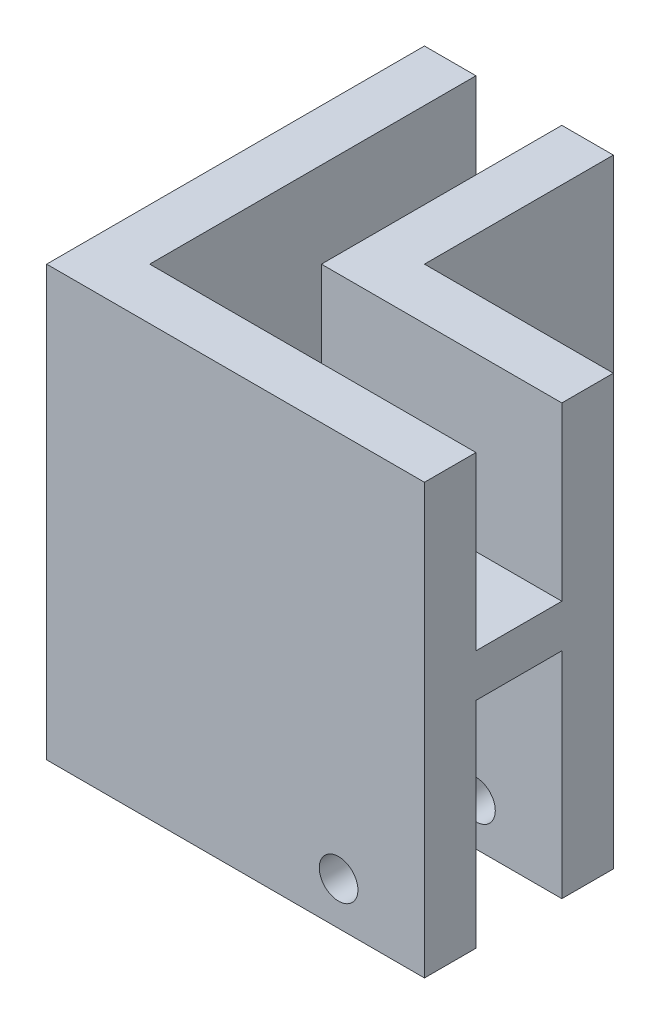
SolidWorks part; units mm, degrees
material "ABS"
ref_plane "Piano frontale" through (0, 0, 0) normal (0, 0, 1) x (1, 0, 0)
ref_plane "Piano superiore" through (0, 0, 0) normal (0, 1, 0) x (1, 0, 0)
ref_plane "Piano destro" through (0, 0, 0) normal (1, 0, 0) x (0, 0, -1)
sketch "Schizzo2" plane through (0, 0, 0) normal (0, 0, 1) x (1, 0, 0)
  line L0 (0, 0) -> (-10, 0)
  line L1 (-10, 0) -> (-10, -25)
  line L2 (-10, -25) -> (-16, -25)
  line L3 (-16, -25) -> (-16, 25)
  line L4 (-16, 25) -> (-10, 25)
  line L5 (-10, 25) -> (-10, 5)
  line L6 (-10, 5) -> (0, 5)
  line L7 (0, 5) -> (0, 25)
  line L8 (0, 25) -> (6, 25)
  line L9 (6, 25) -> (6, -25)
  line L10 (6, -25) -> (0, -25)
  line L11 (0, -25) -> (0, 0)
  dimension "D1" = 5
  dimension "D2" = 50
  dimension "D3" = 6
  dimension "D4" = 10
  dimension "D5" = 25
extrude "Estrusione-Estrusione1" add sketch "Schizzo2" along normal blind 28
sketch "Schizzo3" plane through (6, 0, 0) normal (1, 0, 0) x (0, 0, -1)
  line L3 (-28, 0) -> (-38, 0)
  line L4 (-38, 0) -> (-38, -25)
  line L5 (-38, -25) -> (-44, -25)
  line L6 (-44, -25) -> (-44, 25)
  line L7 (-44, 25) -> (-38, 25)
  line L8 (-38, 25) -> (-38, 5)
  line L9 (-38, 5) -> (-28, 5)
  line L12 (-28, -25) -> (-28, 25) construction
  line L13 (-38, 25) -> (-28, 25) construction
  line L14 (-28, 5) -> (-28, 0)
  dimension "D1" = 5
  dimension "D2" = 6
  dimension "D3" = 50
  dimension "D4" = 10
  dimension "D5" = 25
extrude "Estrusione-Estrusione2" add sketch "Schizzo3" against normal blind 16
sketch "Schizzo4" plane through (-10, 0, 0) normal (-1, 0, 0) x (0, 0, 1)
  line L0 (28, 25) -> (44, 25)
  line L1 (44, 25) -> (44, -25)
  line L2 (44, -25) -> (28, -25)
  line L3 (28, -25) -> (28, 25)
extrude "Estrusione-Estrusione3" add sketch "Schizzo4" along normal blind 6
sketch "Schizzo5" plane through (6, 0, 0) normal (1, 0, 0) x (0, 0, -1)
  line L0 (-38, -25) -> (-44, -25)
  line L1 (-44, -25) -> (-44, 25)
  line L2 (-44, 25) -> (-38, 25)
  line L3 (-38, 25) -> (-38, 5)
  line L4 (-38, 5) -> (-28, 5)
  line L5 (-38, 5) -> (0, 5) construction
  line L6 (-28, 5) -> (-38, 5) construction
  line L7 (-28, 5) -> (-28, 25)
  line L8 (-28, 25) -> (-22, 25)
  line L9 (-28, 25) -> (0, 25) construction
  line L10 (-22, 25) -> (-22, -25)
  line L11 (-28, -25) -> (0, -25) construction
  line L12 (-22, -25) -> (-28, -25)
  line L13 (-28, -25) -> (-28, 0)
  line L14 (-28, 0) -> (-38, 0)
  line L15 (-38, 0) -> (-38, -25)
extrude "Estrusione-Estrusione4" add sketch "Schizzo5" along normal blind 22
hole_wizard "Foro per Vite M4-1" positions "Schizzo6" profile "Schizzo7" hole size "M4" standard "ISO"
sketch "Schizzo6" plane through (0, 0, 44) normal (0, 0, 1) x (1, 0, 0)
  line L0 (-16, -25) -> (-16, 25) construction
  point P0 (18, -20)
  dimension "D1" = 34
  dimension "D2" = 20
sketch "Schizzo7" plane through (18, -20, 44) normal (1, 0, 0) x (0, -1, 0)
  line L0 (0, 0) -> (0, 31.3519)
  line L1 (0, 31.3519) -> (2.25, 30)
  line L2 (2.25, 30) -> (2.25, 0)
  line L5 (2.25, 0) -> (0, 0)
  line L10 (0, 31.3519) -> (-2.25, 30) construction
  line L11 (0, -6.35) -> (0, 107.95) construction
  dimension "Hole Dia." = 4.5
  dimension "Hole Depth" = 30
  dimension "Drill Angle" = 118
hole_wizard "Foro per Vite M4-2" positions "Schizzo8" profile "Schizzo9" hole size "M4" standard "ISO"
sketch "Schizzo8" plane through (-16, 0, 0) normal (-1, 0, 0) x (0, 0, 1)
  line L0 (44, -25) -> (44, 25) construction
  point P0 (10, -20)
  dimension "D1" = 34
  dimension "D2" = 20
sketch "Schizzo9" plane through (-16, -20, 10) normal (0, 1, 0) x (0, 0, 1)
  line L0 (0, 0) -> (0, 31.3519)
  line L1 (0, 31.3519) -> (2.25, 30)
  line L2 (2.25, 30) -> (2.25, 0)
  line L5 (2.25, 0) -> (0, 0)
  line L10 (0, 31.3519) -> (-2.25, 30) construction
  line L11 (0, -6.35) -> (0, 107.95) construction
  dimension "Hole Dia." = 4.5
  dimension "Hole Depth" = 30
  dimension "Drill Angle" = 118
